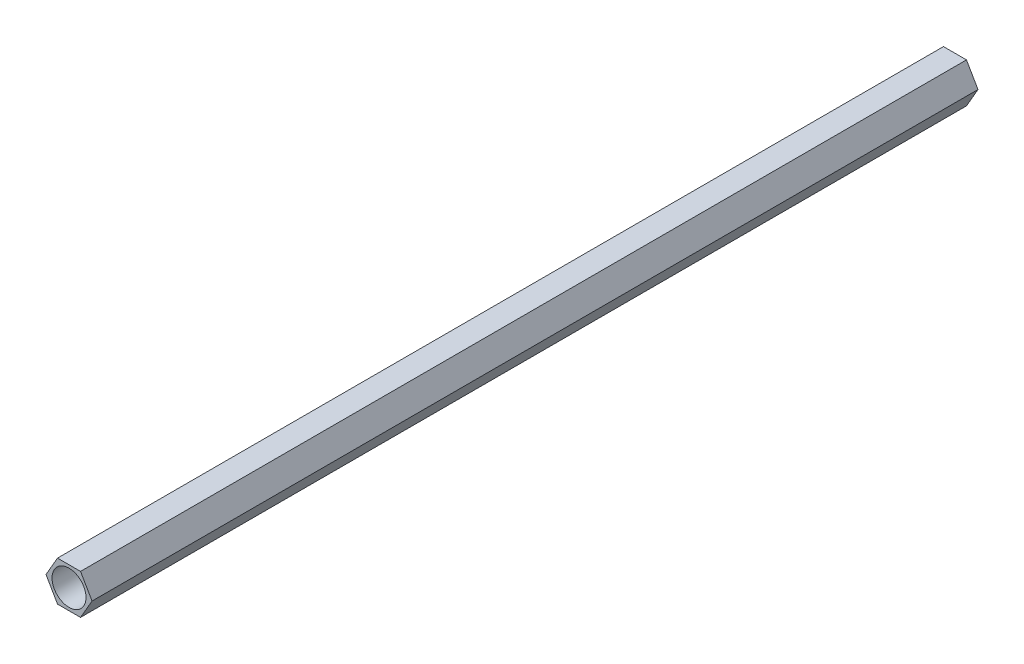
SolidWorks part; units mm, degrees
material "黄铜"
ref_plane "前视基准面" through (0, 0, 0) normal (0, 0, 1) x (1, 0, 0)
ref_plane "上视基准面" through (0, 0, 0) normal (0, 1, 0) x (1, 0, 0)
ref_plane "右视基准面" through (0, 0, 0) normal (1, 0, 0) x (0, 0, -1)
sketch "草图1" plane through (0, 0, 0) normal (0, 0, 1) x (1, 0, 0)
  line L17 (2.5981, 0) -> (1.299, 2.25)
  line L18 (1.299, 2.25) -> (-1.299, 2.25)
  line L19 (-1.299, 2.25) -> (-2.5981, 0)
  line L20 (-2.5981, 0) -> (-1.299, -2.25)
  line L21 (-1.299, -2.25) -> (1.299, -2.25)
  line L22 (1.299, -2.25) -> (2.5981, 0)
  circle A2 centre (0, 0) radius 1.9171
  circle A3 centre (0, 0) radius 2.25 construction
  dimension "D1" = 4.5
extrude "凸台-拉伸1" add sketch "草图1" along normal blind 100
